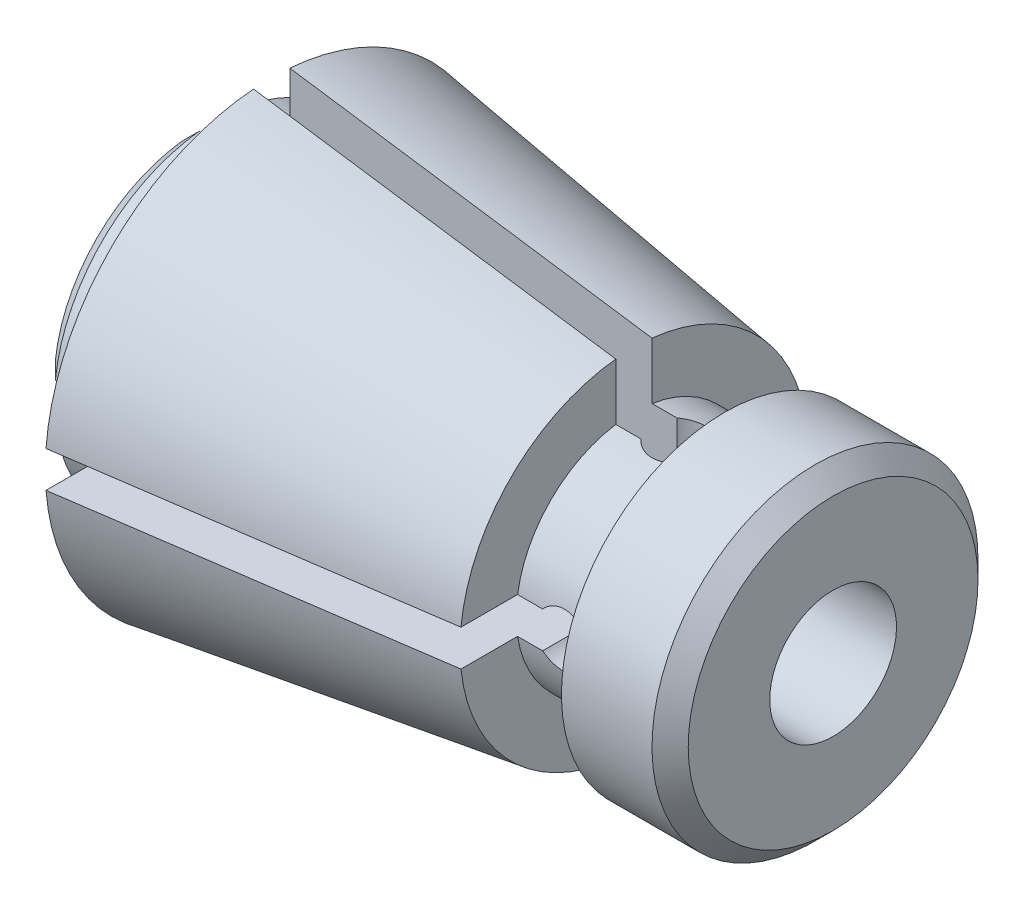
SolidWorks part; units mm, degrees
ref_plane "前视基准面" through (0, 0, 0) normal (0, 0, 1) x (1, 0, 0)
ref_plane "上视基准面" through (0, 0, 0) normal (0, 1, 0) x (1, 0, 0)
ref_plane "右视基准面" through (0, 0, 0) normal (1, 0, 0) x (0, 0, -1)
sketch "草图1" plane through (0, 0, 0) normal (0, 0, 1) x (1, 0, 0)
  line L0 (0, 0) -> (0, 9)
  line L1 (0, -55) -> (0, 55) construction
  line L2 (0, 9) -> (4, 9)
  line L3 (4, 9) -> (4, 12.5)
  line L4 (4, 12.5) -> (24, 9.6001)
  line L5 (24, 9.6001) -> (24, 6.5)
  line L6 (24, 6.5) -> (29, 6.5)
  line L7 (29, 6.5) -> (29, 9)
  line L8 (29, 9) -> (35, 9)
  line L9 (35, 9) -> (35, 0)
  line L10 (35, 0) -> (0, 0) construction
  line L11 (0, 0) -> (35, 0)
  point P12 (64.1718, 2.9099)
  point P14 (64.057, 9.8065)
  dimension "D1" = 18
  dimension "D2" = 25
  dimension "D3" = 13
  dimension "D4" = 18
  dimension "D5" = 35
  dimension "D6" = 4
  dimension "D7" = 5
  dimension "D8" = 20
  dimension "D9" = 8.25
revolve "旋转1" add sketch "草图1" angle 360 about L10
chamfer "倒角1" distance 1 angle 45 2 edges at (35, 9, 0) (0, 9, 0)
sketch "草图2" plane through (0, 0, 0) normal (0, 0, 1) x (1, 0, 0)
  line L0 (13.75, 0) -> (-13.75, 0) construction
  line L1 (29, 6.5) -> (29, -6.5) construction
  circle A0 centre (26.5, 0) radius 1.5
  dimension "D1" = 3
  dimension "D2" = 2.5
extrude "切除-拉伸1" cut sketch "草图2" against normal through all both and the other way through all
sketch "草图3" plane through (0, 0, 0) normal (0, 0, 1) x (1, 0, 0)
  line L0 (26.5, 0) -> (-3.5679, 0)
  line L1 (13.75, 0) -> (-13.75, 0) construction
extrude "切除-拉伸-薄壁1" cut sketch "草图3" against normal through all both and the other way through all thin thin type mid plane wall 2
pattern_circular "阵列(圆周)1" count 4 over 360 about axis through (35, 0, 0) along (1, 0, 0) of "切除-拉伸-薄壁1", "切除-拉伸1"
sketch "草图4" plane through (35, 0, 0) normal (1, 0, 0) x (0, 0, -1)
  circle A0 centre (0, 0) radius 3.5
  dimension "D1" = 7
extrude "切除-拉伸2" cut sketch "草图4" against normal through all both and the other way through all
